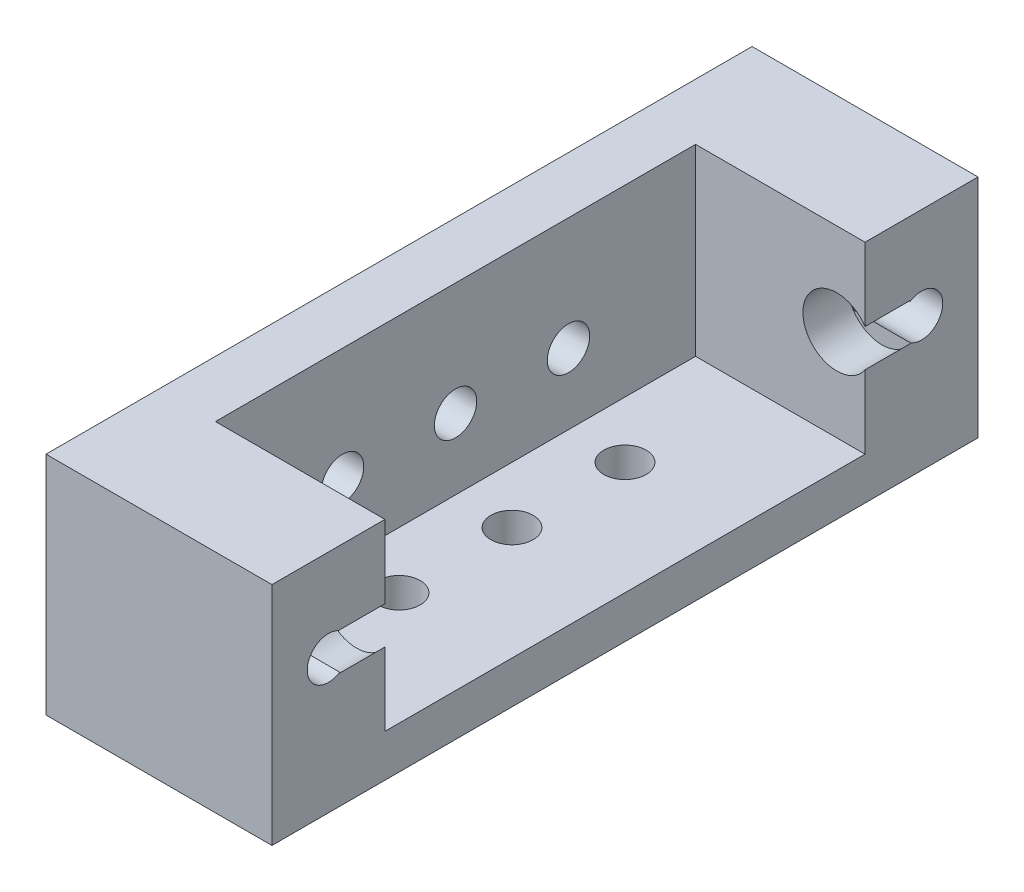
SolidWorks part; units mm, degrees
ref_plane "Front Plane" through (0, 0, 0) normal (0, 0, 1) x (1, 0, 0)
ref_plane "Top Plane" through (0, 0, 0) normal (0, 1, 0) x (1, 0, 0)
ref_plane "Right Plane" through (0, 0, 0) normal (1, 0, 0) x (0, 0, -1)
sketch "Sketch1" plane through (0, 0, 0) normal (0, 0, 1) x (1, 0, 0)
  line L1 (0, 0) -> (25.4, 0)
  line L2 (0, 0) -> (0, 25.4)
  line L3 (0, 25.4) -> (25.4, 25.4)
  line L4 (25.4, 0) -> (25.4, 25.4)
  dimension "D1" = 25.4
  dimension "D2" = 25.4
extrude "Boss-Extrude1" add sketch "Sketch1" along normal blind 79.375
sketch "Sketch2" plane through (0, 25.4, 0) normal (0, 1, 0) x (1, 0, 0)
  line L0 (25.4, -79.375) -> (25.4, 0) construction
  line L1 (25.4, -12.7) -> (6.35, -12.7)
  line L2 (25.4, -12.7) -> (25.4, -66.675)
  line L3 (25.4, -66.675) -> (6.35, -66.675)
  line L4 (6.35, -12.7) -> (6.35, -66.675)
  line L5 (25.4, 0) -> (0, 0) construction
  line L6 (25.4, -79.375) -> (0, -79.375) construction
  dimension "D1" = 19.05
  dimension "D2" = 12.7
  dimension "D3" = 12.7
extrude "Cut-Extrude1" cut sketch "Sketch2" against normal offset from surface (20.6375 mm away) 4.7625 up to face at (12.7, 0, 39.6875)
sketch "Sketch3" plane through (0, 0, 0) normal (-1, 0, 0) x (0, 0, 1)
  line L0 (39.6875, 25.4) -> (39.6875, 12.7) construction
  line L1 (79.375, 25.4) -> (0, 25.4) construction
  line L2 (39.6875, 12.7) -> (26.9875, 12.7) construction
  line L3 (39.6875, 12.7) -> (52.3875, 12.7) construction
  circle A0 centre (26.9875, 12.7) radius 2.3813
  circle A1 centre (39.6875, 12.7) radius 2.3812
  circle A2 centre (52.3875, 12.7) radius 2.3812
  dimension "D2" = 4.7625
  dimension "D1" = 12.7
extrude "Cut-Extrude2" cut sketch "Sketch3" against normal through all both and the other way through all
sketch "Sketch4" plane through (0, 0, 0) normal (0, -1, 0) x (1, 0, 0)
  line L0 (0, 39.6875) -> (12.7, 39.6875) construction
  line L1 (0, 79.375) -> (0, 0) construction
  line L2 (12.7, 39.6875) -> (12.7, 52.3875) construction
  line L3 (12.7, 39.6875) -> (12.7, 26.9875) construction
  circle A0 centre (12.7, 52.3875) radius 2.3812
  circle A1 centre (12.7, 39.6875) radius 2.3812
  circle A2 centre (12.7, 26.9875) radius 2.3813
  dimension "D2" = 4.7625
  dimension "D1" = 12.7
extrude "Cut-Extrude3" cut sketch "Sketch4" against normal through all both
sketch "Sketch6" plane through (0, 0, 12.7) normal (0, 0, 1) x (1, 0, 0)
  line L0 (25.4, 4.7625) -> (25.4, 25.4) construction
  line L2 (25.4, 15.0812) -> (22.225, 15.0812) construction
  circle A0 centre (22.225, 15.0812) radius 3.81
  dimension "D1" = 7.62
  dimension "D2" = 3.175
extrude "Cut-Extrude4" cut sketch "Sketch6" against normal blind 5.08 and the other way offset from surface (59.055 mm away) 5.08 contours A0 other way up to face at (15.875, 15.0812, 66.675)
sketch "Sketch8" plane through (25.4, 0, 0) normal (1, 0, 0) x (0, 0, -1)
  line L0 (-79.375, 0) -> (-79.375, 25.4) construction
  line L1 (-71.755, 15.0812) -> (-73.025, 15.0812) construction
  line L2 (-71.755, 11.2712) -> (-71.755, 18.8912) construction
  line L3 (-7.62, 15.0812) -> (-6.35, 15.0812) construction
  line L4 (-7.62, 18.8912) -> (-7.62, 11.2712) construction
  line L5 (0, 0) -> (0, 25.4) construction
  circle A0 centre (-73.025, 15.0812) radius 2.3813
  circle A1 centre (-6.35, 15.0812) radius 2.3813
  dimension "D1" = 4.7625
  dimension "D2" = 6.35
  dimension "D3" = 6.35
extrude "Cut-Extrude5" cut sketch "Sketch8" against normal blind 6.35
